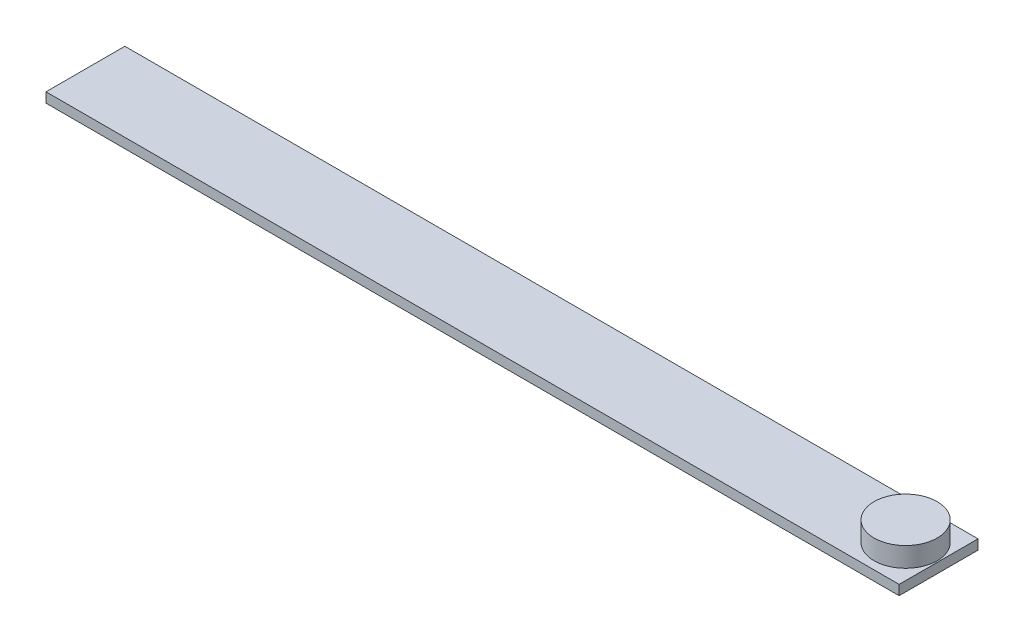
SolidWorks part; units mm, degrees
ref_plane "Front Plane" through (0, 0, 0) normal (0, 0, 1) x (1, 0, 0)
ref_plane "Top Plane" through (0, 0, 0) normal (0, 1, 0) x (1, 0, 0)
ref_plane "Right Plane" through (0, 0, 0) normal (1, 0, 0) x (0, 0, -1)
sketch "Sketch1" plane through (0, 0, 0) normal (0, 0, 1) x (1, 0, 0)
  line L1 (0, 0) -> (274.7645, 0)
  line L2 (0, 0) -> (0, 3.175)
  line L3 (0, 3.175) -> (274.7645, 3.175)
  line L4 (274.7645, 0) -> (274.7645, 3.175)
extrude "Boss-Extrude1" add sketch "Sketch1" along normal blind 25.4
sketch "Sketch2" plane through (0, 3.175, 0) normal (0, 1, 0) x (1, 0, 0)
  circle A0 centre (264.16, -12.7) radius 10.16
extrude "Boss-Extrude2" add sketch "Sketch2" along normal blind 6.35
